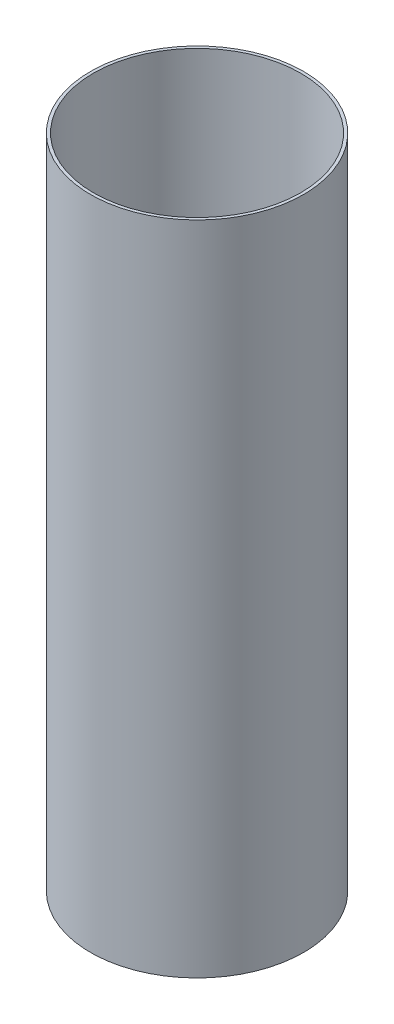
SolidWorks part; units mm, degrees
material "S-Glass Fiber"
ref_plane "Front Plane" through (0, 0, 0) normal (0, 0, 1) x (1, 0, 0)
ref_plane "Top Plane" through (0, 0, 0) normal (0, 1, 0) x (1, 0, 0)
ref_plane "Right Plane" through (0, 0, 0) normal (1, 0, 0) x (0, 0, -1)
sketch "Sketch1" plane through (0, 0, 0) normal (0, 1, 0) x (1, 0, 0)
  circle A0 centre (0, 0) radius 78.359
  circle A1 centre (0, 0) radius 76.2
  dimension "D1" = 152.4
  dimension "D2" = 156.718
extrude "Boss-Extrude1" add sketch "Sketch1" along normal blind 482.6
